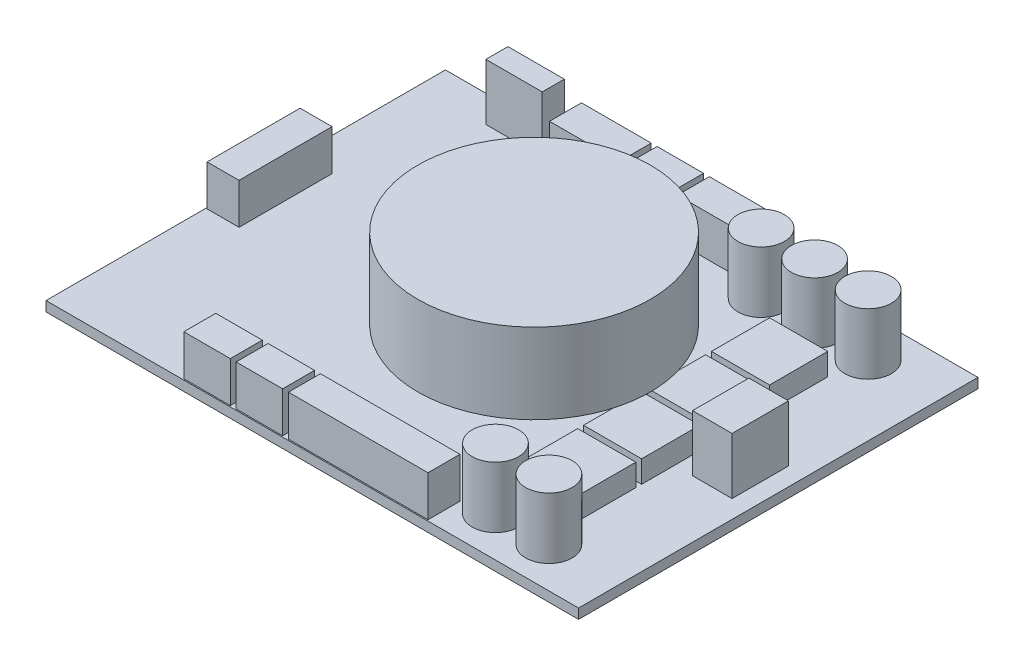
SolidWorks part; units mm, degrees
ref_plane "Front Plane" through (0, 0, 0) normal (0, 0, 1) x (1, 0, 0)
ref_plane "Top Plane" through (0, 0, 0) normal (0, 1, 0) x (1, 0, 0)
ref_plane "Right Plane" through (0, 0, 0) normal (1, 0, 0) x (0, 0, -1)
sketch "Sketch1" plane through (0, 0, 0) normal (0, 1, 0) x (1, 0, 0)
  line L1 (45.8, -34.35) -> (-45.8, -34.35)
  line L2 (45.8, -34.35) -> (45.8, 34.35)
  line L3 (45.8, 34.35) -> (-45.8, 34.35)
  line L4 (-45.8, -34.35) -> (-45.8, 34.35)
  line L5 (45.8, -34.35) -> (-45.8, 34.35) construction
  line L6 (45.8, 34.35) -> (-45.8, -34.35) construction
  point P0 (0, 0)
  dimension "D1" = 91.6
  dimension "D2" = 68.7
extrude "Boss-Extrude1" add sketch "Sketch1" along normal blind 1.7
sketch "Sketch2" plane through (0, 1.7, 0) normal (0, 1, 0) x (1, 0, 0)
  line L0 (45.8, -34.35) -> (45.8, 34.35) construction
  circle A0 centre (3.8, 0) radius 20
  point P5 (0, 0)
  dimension "D1" = 40
  dimension "D2" = 42
extrude "Boss-Extrude2" add sketch "Sketch2" along normal offset from surface (13.8 mm away) 17.8 from offset 4 up to face at (0, 1.7, 0) offset beyond the face yes
sketch "Sketch3" plane through (0, 1.7, 0) normal (0, 1, 0) x (1, 0, 0)
  line L0 (45.8, -34.35) -> (45.8, 34.35) construction
  line L2 (45.8, 34.35) -> (-45.8, 34.35) construction
  line L3 (-45.8, -34.35) -> (45.8, -34.35) construction
  circle A2 centre (15.4, 27.45) radius 4
  circle A3 centre (24.6, 27.45) radius 4
  circle A4 centre (33.8, 27.45) radius 4
  circle A5 centre (33.8, -27.45) radius 4
  circle A6 centre (24.6, -27.45) radius 4
  point P1 (37.8, 27.45)
  point P10 (13.2905, 42.5285)
  point P14 (15.4, 31.45)
  point P19 (0, 0)
  point P20 (33.8, -31.45)
  dimension "D1" = 8
  dimension "D2" = 3
  dimension "D6" = 2.9
  dimension "D3" = 18.4
  dimension "D4" = 8
  dimension "D5" = 2.9
extrude "Boss-Extrude3" add sketch "Sketch3" along normal blind 10.5
sketch "Sketch4" plane through (0, 1.7, 0) normal (0, 1, 0) x (1, 0, 0)
  line L0 (32.8, 10.5) -> (32.8, 0.5)
  line L1 (32.8, 21.5) -> (22.8, 21.5)
  line L2 (32.8, 21.5) -> (32.8, 11.5)
  line L3 (32.8, 11.5) -> (22.8, 11.5)
  line L4 (22.8, 21.5) -> (22.8, 11.5)
  line L5 (32.8, 10.5) -> (22.8, 10.5)
  line L6 (22.8, 10.5) -> (22.8, 0.5)
  line L7 (32.8, 0.5) -> (22.8, 0.5)
  line L8 (32.8, -0.5) -> (32.8, -10.5)
  line L9 (32.8, -0.5) -> (22.8, -0.5)
  line L10 (22.8, -0.5) -> (22.8, -10.5)
  line L11 (32.8, -10.5) -> (22.8, -10.5)
  line L12 (32.8, -11.5) -> (32.8, -21.5)
  line L13 (32.8, -11.5) -> (22.8, -11.5)
  line L14 (22.8, -11.5) -> (22.8, -21.5)
  line L15 (32.8, -21.5) -> (22.8, -21.5)
  line L16 (27.8, 21.5) -> (27.8, -21.5) construction
  line L17 (27.8, 0) -> (0, 0) construction
  line L18 (45.8, -34.35) -> (45.8, 34.35) construction
  dimension "D1" = 10
  dimension "D2" = 4
  dimension "D3" = 43
  dimension "D4" = 13
extrude "Boss-Extrude4" add sketch "Sketch4" along normal blind 3.8
sketch "Sketch6" plane through (0, 19.5, 0) normal (0, 1, 0) x (1, 0, 0)
  circle A0 centre (3.8, 0) radius 10
  dimension "D1" = 20
extrude "Boss-Extrude5" add sketch "Sketch6" against normal up to surface (17.8 mm away) up to face at (24.6, 1.7, 31.45)
sketch "Sketch7" plane through (0, 1.7, 0) normal (0, 1, 0) x (1, 0, 0)
  line L0 (35.9, 0) -> (0, 0) construction
  line L1 (35.9, 4.85) -> (42.7, 4.85)
  line L2 (35.9, 4.85) -> (35.9, -4.85)
  line L3 (35.9, -4.85) -> (42.7, -4.85)
  line L4 (42.7, 4.85) -> (42.7, -4.85)
  line L5 (45.8, -34.35) -> (45.8, 34.35) construction
  line L6 (45.8, 34.35) -> (-45.8, 34.35) construction
  line L7 (-34.2, 33.5) -> (-24.5, 33.5)
  line L8 (-34.2, 33.5) -> (-34.2, 29.7)
  line L9 (-34.2, 29.7) -> (-24.5, 29.7)
  line L10 (-24.5, 33.5) -> (-24.5, 29.7)
  line L11 (-45.8, 34.35) -> (-45.8, -34.35) construction
  point P13 (-29.35, 29.7)
  dimension "D1" = 9.7
  dimension "D2" = 6.8
  dimension "D3" = 3.1
  dimension "D4" = 3.8
  dimension "D5" = 9.7
  dimension "D6" = 0.85
  dimension "D7" = 11.6
extrude "Boss-Extrude6" add sketch "Sketch7" along normal blind 9.7
sketch "Sketch8" plane through (0, 1.7, 0) normal (0, 1, 0) x (1, 0, 0)
  line L0 (-45.8, -34.35) -> (45.8, -34.35) construction
  line L1 (-4.3, -28.65) -> (19.7, -28.65)
  line L2 (-4.3, -28.65) -> (-4.3, -34.15)
  line L3 (-4.3, -34.15) -> (19.7, -34.15)
  line L4 (19.7, -28.65) -> (19.7, -34.15)
  line L5 (-5.3, -28.65) -> (-13.3, -28.65)
  line L6 (-5.3, -28.65) -> (-5.3, -34.15)
  line L7 (-5.3, -34.15) -> (-13.3, -34.15)
  line L8 (-13.3, -28.65) -> (-13.3, -34.15)
  line L9 (-14.3, -28.65) -> (-22.3, -28.65)
  line L10 (-14.3, -28.65) -> (-14.3, -34.15)
  line L11 (-14.3, -34.15) -> (-22.3, -34.15)
  line L12 (-22.3, -28.65) -> (-22.3, -34.15)
  line L15 (-45.8, 34.35) -> (-45.8, -34.35) construction
  line L16 (45.8, 34.35) -> (-45.8, 34.35) construction
  line L17 (-45.6, 9.15) -> (-40.1, 9.15)
  line L18 (-45.6, 9.15) -> (-45.6, -6.85)
  line L19 (-45.6, -6.85) -> (-40.1, -6.85)
  line L20 (-40.1, 9.15) -> (-40.1, -6.85)
  line L21 (-22.2, 34.15) -> (-10.2, 34.15)
  line L22 (-22.2, 34.15) -> (-22.2, 28.65)
  line L23 (-22.2, 28.65) -> (-10.2, 28.65)
  line L24 (-10.2, 34.15) -> (-10.2, 28.65)
  line L25 (-9.2, 34.15) -> (-1.2, 34.15)
  line L26 (-9.2, 34.15) -> (-9.2, 28.65)
  line L27 (-9.2, 28.65) -> (-1.2, 28.65)
  line L28 (-1.2, 34.15) -> (-1.2, 28.65)
  line L29 (-0.2, 34.15) -> (9.8, 34.15)
  line L30 (-0.2, 34.15) -> (-0.2, 28.65)
  line L31 (-0.2, 28.65) -> (9.8, 28.65)
  line L32 (9.8, 34.15) -> (9.8, 28.65)
  line L33 (45.8, -34.35) -> (45.8, 34.35) construction
  dimension "D1" = 0.2
  dimension "D2" = 24
  dimension "D3" = 8
  dimension "D4" = 1
  dimension "D5" = 1
  dimension "D6" = 23.5
  dimension "D7" = 5.5
  dimension "D8" = 27.5
  dimension "D9" = 16
  dimension "D10" = 0.2
  dimension "D11" = 1
  dimension "D12" = 1
  dimension "D13" = 10
  dimension "D14" = 8
  dimension "D15" = 12
  dimension "D16" = 0.2
  dimension "D17" = 36
extrude "Boss-Extrude7" add sketch "Sketch8" along normal blind 7
